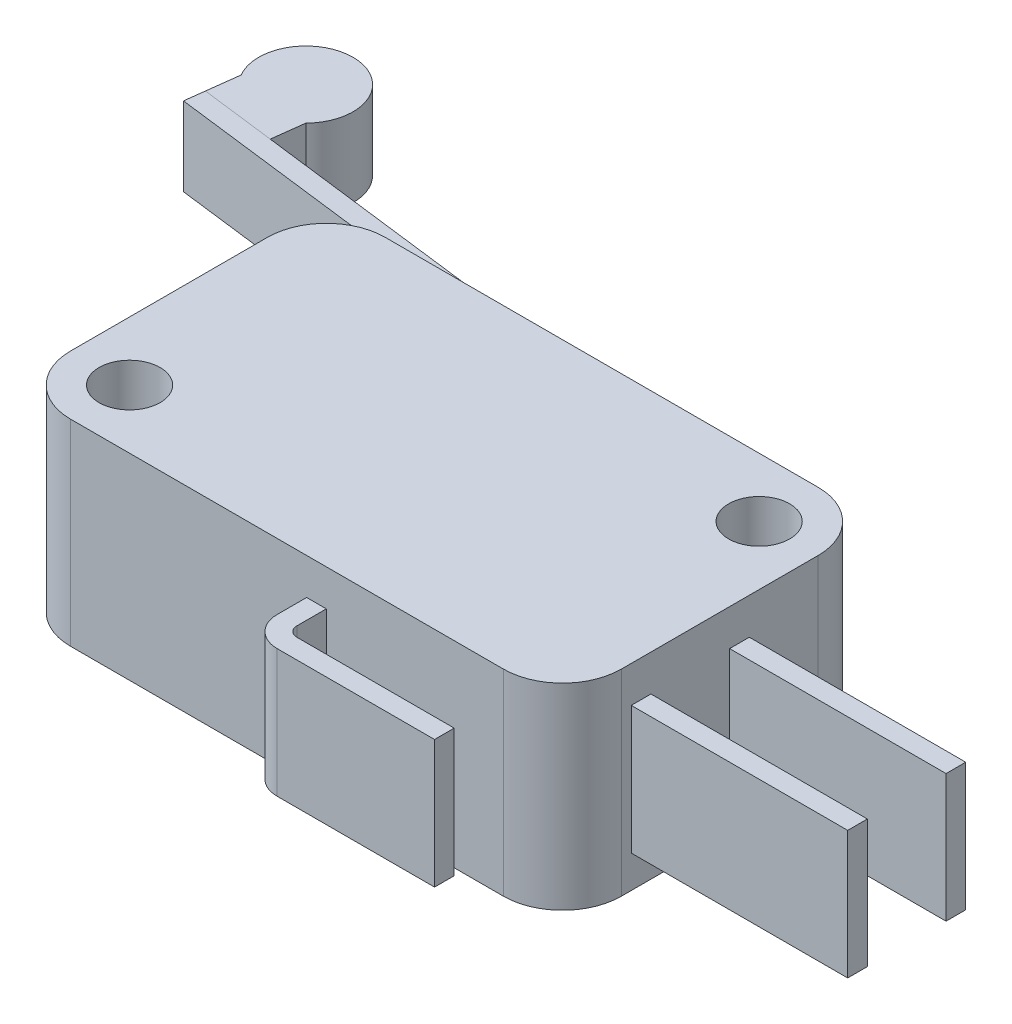
SolidWorks part; units mm, degrees
ref_plane "前视基准面" through (0, 0, 0) normal (0, 0, 1) x (1, 0, 0)
ref_plane "上视基准面" through (0, 0, 0) normal (0, 1, 0) x (1, 0, 0)
ref_plane "右视基准面" through (0, 0, 0) normal (1, 0, 0) x (0, 0, -1)
sketch "草图1" plane through (0, 0, 0) normal (0, 1, 0) x (1, 0, 0)
  line L1 (0, 0) -> (28, 0)
  line L2 (0, 0) -> (0, 16)
  line L3 (0, 16) -> (28, 16)
  line L4 (28, 0) -> (28, 16)
  circle A0 centre (25, 13) radius 1.55
  circle A1 centre (3, 3) radius 1.55
  dimension "D3" = 3.1
  dimension "D1" = 16
  dimension "D2" = 28
  dimension "D4" = 22
  dimension "D5" = 10
  dimension "D6" = 3
  dimension "D7" = 3
extrude "凸台-拉伸1" add sketch "草图1" along normal blind 10
fillet "圆角1" radius 3 4 edges at (0, 5, -16) (28, 5, -16) (28, 5, 0) (0, 5, 0)
ref_plane "基准面1" through (0, 4.9, 0) normal (0, 1, 0) x (1, 0, 0)
sketch "草图2" plane through (0, 4.9, 0) normal (0, 1, 0) x (1, 0, 0)
  line L0 (16.4, 13.75) -> (16.7413, 16.4787)
  line L1 (25, 16) -> (3, 16) construction
  line L2 (15.8732, 17.5951) -> (-11.1165, 20.9712)
  line L5 (0, 13) -> (0, 3) construction
  arc A0 (16.7413, 16.4787) -> (15.8732, 17.5951) centre (15.7491, 16.6029) ccw
  point P6 (15.4, 13.5286)
  point P9 (-8.4, 19.7)
  point P10 (0, 0)
  point P11 (-7.3458, 29.5649)
  dimension "D2" = 1
  dimension "D1" = 2.25
  dimension "D3" = 7.13
  dimension "D4" = 27.2
  dimension "D5" = 16.4
  dimension "D6" = 3.75
ref_plane "基准面2" through (16.4, 4.9, -13.75) normal (0.1241, 0, -0.9923) x (-0.9923, 0, -0.1241)
sketch "草图3" plane through (-0.0123, 0, -15.803) normal (0.1241, 0, -0.9923) x (-0.9923, 0, -0.1241)
  line L0 (-15.5402, 4.9) -> (-16.5402, 4.9) construction
  line L1 (-15.5402, 6.9) -> (-16.5402, 6.9)
  line L2 (-15.5402, 6.9) -> (-15.5402, 2.9)
  line L3 (-15.5402, 2.9) -> (-16.5402, 2.9)
  line L4 (-16.5402, 6.9) -> (-16.5402, 2.9)
  point P4 (-15.5402, 4.9)
  point P7 (-14.7502, 6.9)
  dimension "D1" = 4
  dimension "D2" = 1
sweep "扫描1" add profiles "草图3" path "草图2"
sketch "草图4" plane through (0, 6.9, 0) normal (0, 1, 0) x (1, 0, 0)
  line L0 (-11.1165, 20.9712) -> (-10.9145, 22.5861)
  line L1 (-11.1165, 20.9712) -> (-7.3526, 20.5004)
  line L2 (15.8732, 17.5951) -> (-11.1165, 20.9712) construction
  line L3 (-7.3526, 20.5004) -> (-7.1506, 22.1153)
  line L4 (0, 13) -> (0, 3) construction
  line L5 (25, 16) -> (3, 16) construction
  arc A0 (-10.9145, 22.5861) -> (-7.1506, 22.1153) centre (-8.85, 23.81) cw
  dimension "D1" = 2.4
  dimension "D2" = 8.85
  dimension "D3" = 7.81
extrude "凸台-拉伸2" add sketch "草图4" against normal up to surface (4 mm away) separate body up to face at (2.3163, 2.9, -18.787)
sketch "草图5" plane through (0, 4.9, 0) normal (0, 1, 0) x (1, 0, 0)
  line L0 (15.5, 0) -> (15.5, -1.5)
  line L1 (3, 0) -> (25, 0) construction
  line L2 (16.5, -2.5) -> (24.5, -2.5)
  line L3 (28, 3) -> (28, 13) construction
  line L4 (28, 4) -> (39, 4)
  line L5 (28, 9) -> (39, 9)
  arc A0 (15.5, -1.5) -> (16.5, -2.5) centre (16.5, -1.5) ccw
  dimension "D3" = 1
  dimension "D1" = 12.5
  dimension "D2" = 2.5
  dimension "D4" = 9
  dimension "D5" = 4
  dimension "D6" = 5
  dimension "D7" = 11
extrude "拉伸-薄壁1" add sketch "草图5" along normal mid plane 6.5 thin thin type mid plane wall 1
